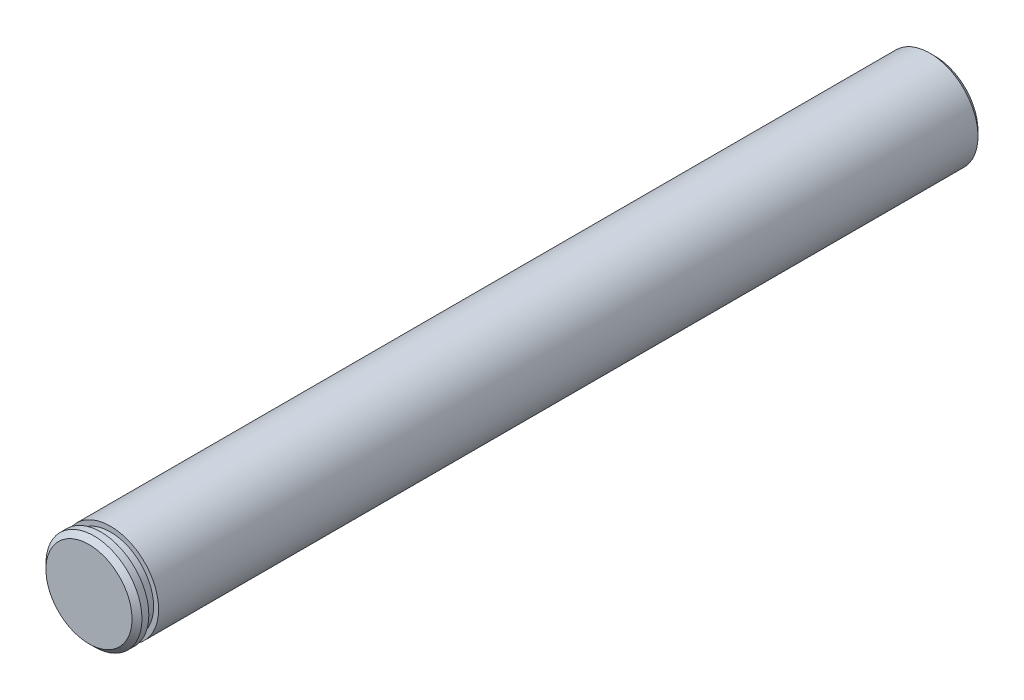
SolidWorks part; units mm, degrees
ref_plane "Front Plane" through (0, 0, 0) normal (0, 0, 1) x (1, 0, 0)
ref_plane "Top Plane" through (0, 0, 0) normal (0, 1, 0) x (1, 0, 0)
ref_plane "Right Plane" through (0, 0, 0) normal (1, 0, 0) x (0, 0, -1)
sketch "Sketch1" plane through (0, 0, 0) normal (0, 0, 1) x (1, 0, 0)
  circle A0 centre (0, 0) radius 4.825
  dimension "D1" = 9.65
extrude "Boss-Extrude1" add sketch "Sketch1" along normal blind 85
chamfer "Chamfer1" distance 0.5 angle 45 1 edges at (4.825, 0, 85)
chamfer "Chamfer2" distance 0.5 angle 45 1 edges at (4.825, 0, 0)
sketch "Sketch2" plane through (0, 0, 0) normal (0, 1, 0) x (1, 0, 0)
  line L0 (-4.825, -0.5) -> (-4.825, -84.5) construction
  line L1 (-4.825, -83.81) -> (-4.325, -83.81)
  line L2 (-4.825, -83.81) -> (-4.825, -82.83)
  line L3 (-4.825, -82.83) -> (-4.325, -82.83)
  line L4 (-4.325, -83.81) -> (-4.325, -82.83)
  line L5 (4.825, -84.5) -> (-4.825, -84.5) construction
  line L6 (0, -85) -> (0, -82.5514) construction
  line L7 (-4.325, -85) -> (4.325, -85) construction
  dimension "D1" = 0.98
  dimension "D2" = 0.5
  dimension "D3" = 0.69
revolve "Cut-Revolve1" cut sketch "Sketch2" angle 360 about L6
